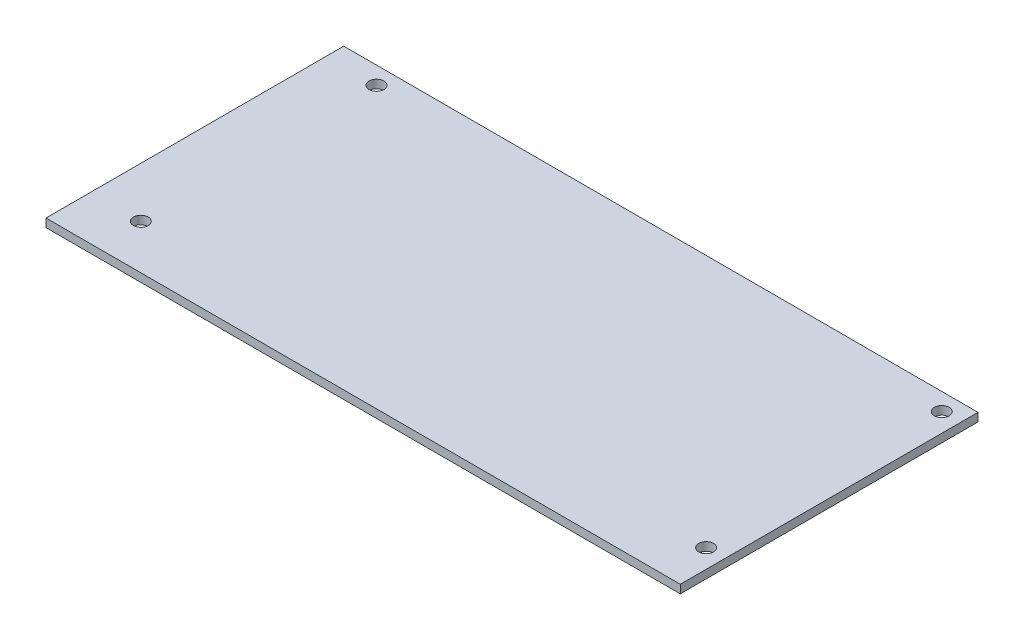
SolidWorks part; units mm, degrees
ref_plane "Front Plane" through (0, 0, 0) normal (0, 0, 1) x (1, 0, 0)
ref_plane "Top Plane" through (0, 0, 0) normal (0, 1, 0) x (1, 0, 0)
ref_plane "Right Plane" through (0, 0, 0) normal (1, 0, 0) x (0, 0, -1)
sketch "Sketch1" plane through (0, 0, 0) normal (0, 1, 0) x (1, 0, 0)
  line L1 (68.5, 32.15) -> (-68.5, 32.15)
  line L2 (68.5, 32.15) -> (68.5, -32.15)
  line L3 (68.5, -32.15) -> (-68.5, -32.15)
  line L4 (-68.5, 32.15) -> (-68.5, -32.15)
  line L5 (68.5, 32.15) -> (-68.5, -32.15) construction
  line L6 (68.5, -32.15) -> (-68.5, 32.15) construction
  point P0 (0, 0)
  dimension "D1" = 137
  dimension "D2" = 64.3
extrude "Boss-Extrude1" add sketch "Sketch1" along normal blind 1.8
sketch "Sketch2" plane through (0, 1.8, 0) normal (0, 1, 0) x (1, 0, 0)
  line L0 (68.5, 32.15) -> (64.45, 32.15) construction
  line L1 (68.5, 32.15) -> (-68.5, 32.15) construction
  line L2 (64.45, 32.15) -> (64.45, 28.38) construction
  line L3 (64.45, 28.38) -> (64.45, -22.52) construction
  line L6 (-57.65, 28.38) -> (-57.65, -22.52) construction
  line L8 (64.45, 32.15) -> (-57.65, 32.15) construction
  line L9 (-57.65, 32.15) -> (-57.65, 28.38) construction
  circle A0 centre (-57.65, 28.38) radius 1.6
  circle A1 centre (-57.65, -22.52) radius 1.6
  circle A2 centre (64.45, 28.38) radius 1.6
  circle A3 centre (64.45, -22.52) radius 1.6
  point P6 (65.9154, -22.75)
  dimension "D1" = 122.1
  dimension "D2" = 3.77
  dimension "D3" = 3.77
  dimension "D4" = 4.05
  dimension "D5" = 50.9
  dimension "D7" = 50.9
extrude "Cut-Extrude1" cut sketch "Sketch2" against normal blind 2
